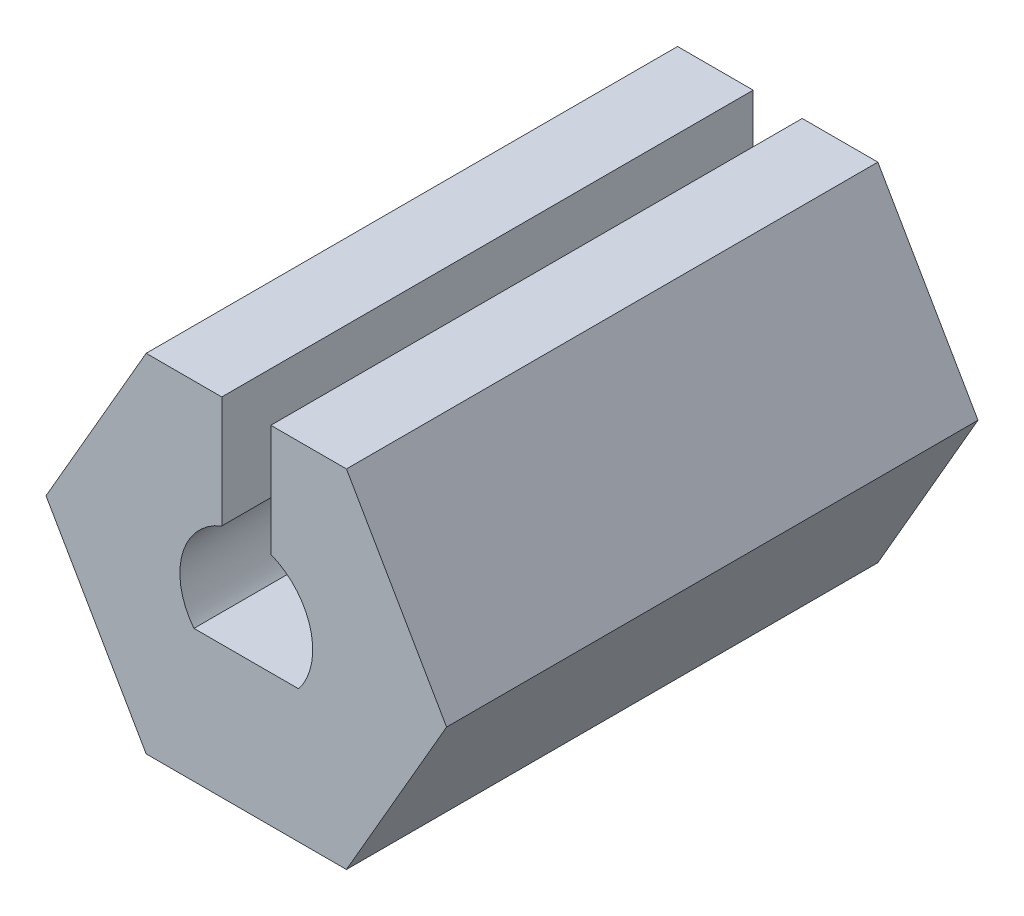
SolidWorks part; units mm, degrees
ref_plane "Front Plane" through (0, 0, 0) normal (0, 0, 1) x (1, 0, 0)
ref_plane "Top Plane" through (0, 0, 0) normal (0, 1, 0) x (1, 0, 0)
ref_plane "Right Plane" through (0, 0, 0) normal (1, 0, 0) x (0, 0, -1)
sketch "Sketch1" plane through (0, 0, 0) normal (0, 0, 1) x (1, 0, 0)
  line L0 (-1.2809, -1) -> (1.2809, -1)
  line L1 (4.9, 0) -> (2.45, 4.2435)
  line L2 (2.45, 4.2435) -> (-2.45, 4.2435)
  line L3 (-2.45, 4.2435) -> (-4.9, 0)
  line L4 (-4.9, 0) -> (-2.45, -4.2435)
  line L5 (-2.45, -4.2435) -> (2.45, -4.2435)
  line L6 (2.45, -4.2435) -> (4.9, 0)
  line L7 (0, 0) -> (0, 4.2435) construction
  line L8 (-0.6, 4.2435) -> (-0.6, 1.5102)
  line L9 (0.6, 4.2435) -> (0.6, 1.5102)
  circle A0 centre (0, 0) radius 4.9 construction
  circle A1 centre (0, 0) radius 1.625
  dimension "D1" = 9.8
  dimension "D2" = 3.25
  dimension "D3" = 1
  dimension "D4" = 0.6
  dimension "D5" = 0.6
  dimension "D6" = 8.487
extrude "Boss-Extrude1" add sketch "Sketch1" along normal blind 13 contours A1 L8 L2 L3 L4 L5 L6 L1 L9 | L0 A1
